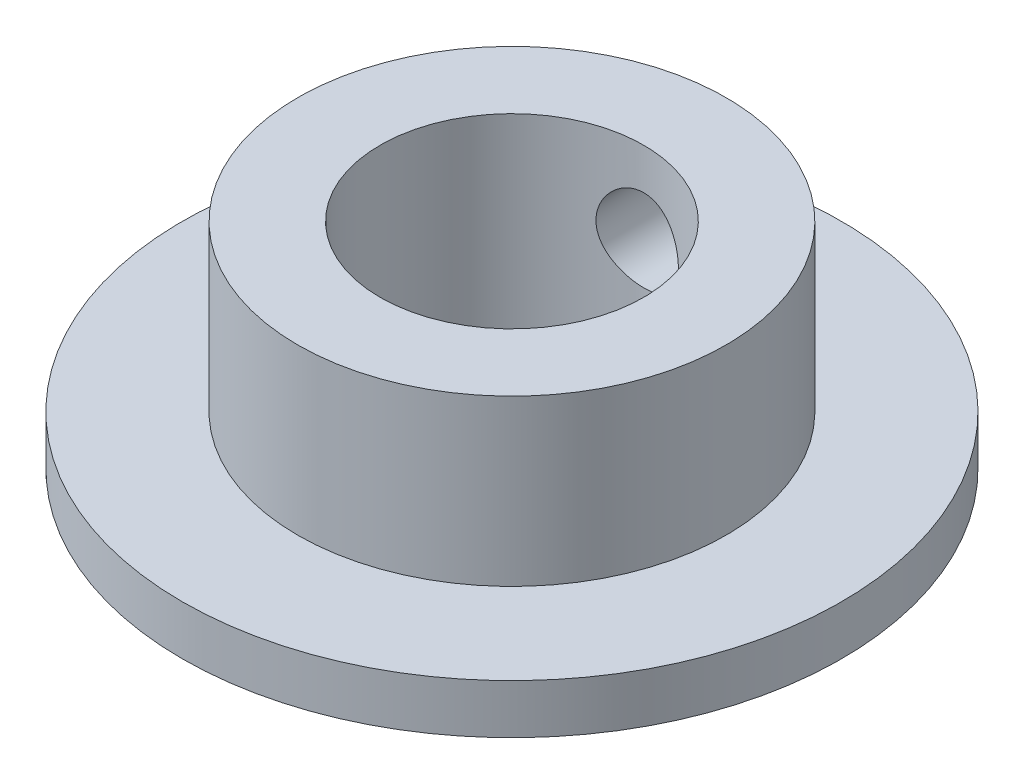
SolidWorks part; units mm, degrees
ref_plane "Front Plane" through (0, 0, 0) normal (0, 0, 1) x (1, 0, 0)
ref_plane "Top Plane" through (0, 0, 0) normal (0, 1, 0) x (1, 0, 0)
ref_plane "Right Plane" through (0, 0, 0) normal (1, 0, 0) x (0, 0, -1)
sketch "Sketch1" plane through (0, 0, 0) normal (0, 1, 0) x (1, 0, 0)
  circle A0 centre (0, 0) radius 8
  circle A1 centre (0, 0) radius 20
  dimension "D1" = 16
  dimension "D2" = 40
extrude "Boss-Extrude1" add sketch "Sketch1" along normal blind 3
sketch "Sketch2" plane through (0, 3, 0) normal (0, 1, 0) x (1, 0, 0)
  circle A1 centre (0, 0) radius 8 construction
  circle A2 centre (0, 0) radius 13
  circle A3 centre (0, 0) radius 13
  circle A4 centre (0, 0) radius 8
  dimension "D1" = 5
extrude "Boss-Extrude2" add sketch "Sketch2" along normal blind 10
sketch "Sketch3" plane through (0, 0, 0) normal (0, 0, 1) x (1, 0, 0)
  line L0 (-13, 8) -> (13, 8) construction
  line L1 (-13, 13) -> (-13, 3) construction
  line L2 (13, 3) -> (13, 13) construction
  circle A0 centre (0, 8) radius 2.5
  point P8 (0, 0)
  dimension "D1" = 5
extrude "Cut-Extrude1" cut sketch "Sketch3" against normal through all contours A0
